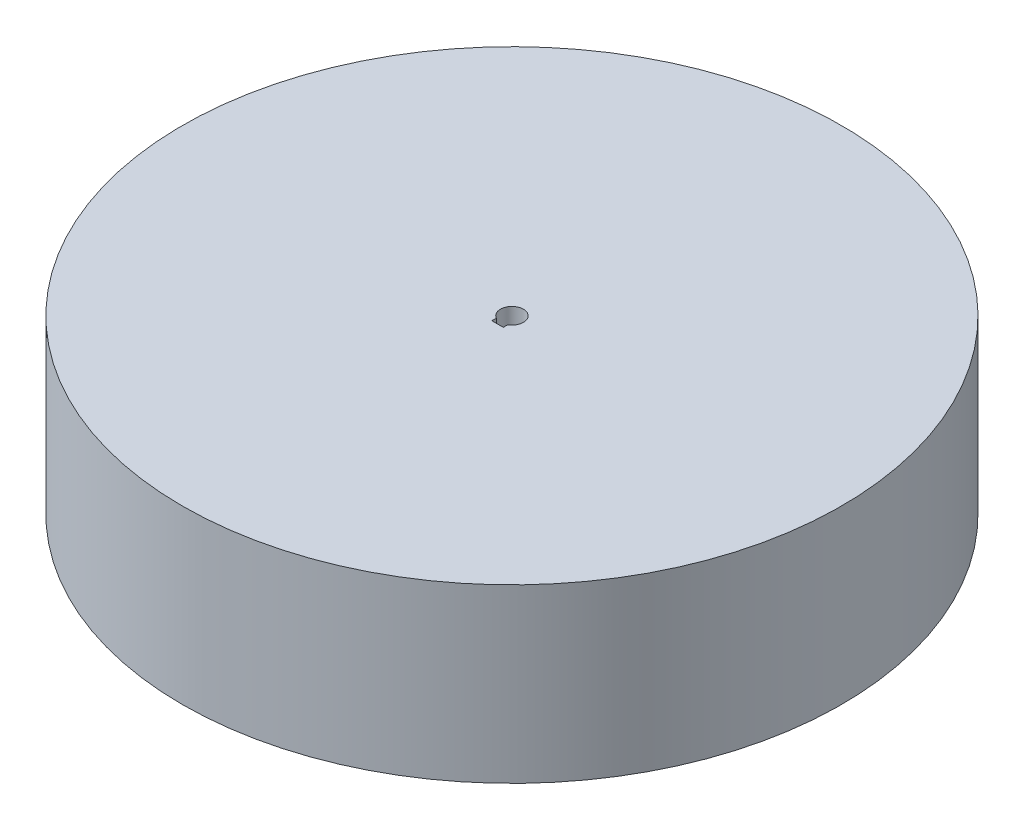
SolidWorks part; units mm, degrees
ref_plane "Front Plane" through (0, 0, 0) normal (0, 0, 1) x (1, 0, 0)
ref_plane "Top Plane" through (0, 0, 0) normal (0, 1, 0) x (1, 0, 0)
ref_plane "Right Plane" through (0, 0, 0) normal (1, 0, 0) x (0, 0, -1)
sketch "Sketch1" plane through (0, 0, 0) normal (0, 1, 0) x (1, 0, 0)
  circle A0 centre (0, 0) radius 57.5
  dimension "D1" = 115
extrude "Boss-Extrude1" add sketch "Sketch1" along normal blind 30
sketch "Sketch2" plane through (0, 0, 0) normal (0, -1, 0) x (1, 0, 0)
  line L0 (0, 0) -> (0, 2.5) construction
  line L1 (1, 2.5) -> (-1, 2.5)
  line L2 (-1, 2.5) -> (-1, 1.7321)
  line L3 (1, 2.5) -> (1, 1.7321)
  circle A0 centre (0, 0) radius 2
  dimension "D1" = 4
  dimension "D2" = 2
  dimension "D3" = 2.5
extrude "Cut-Extrude1" cut sketch "Sketch2" against normal through all
